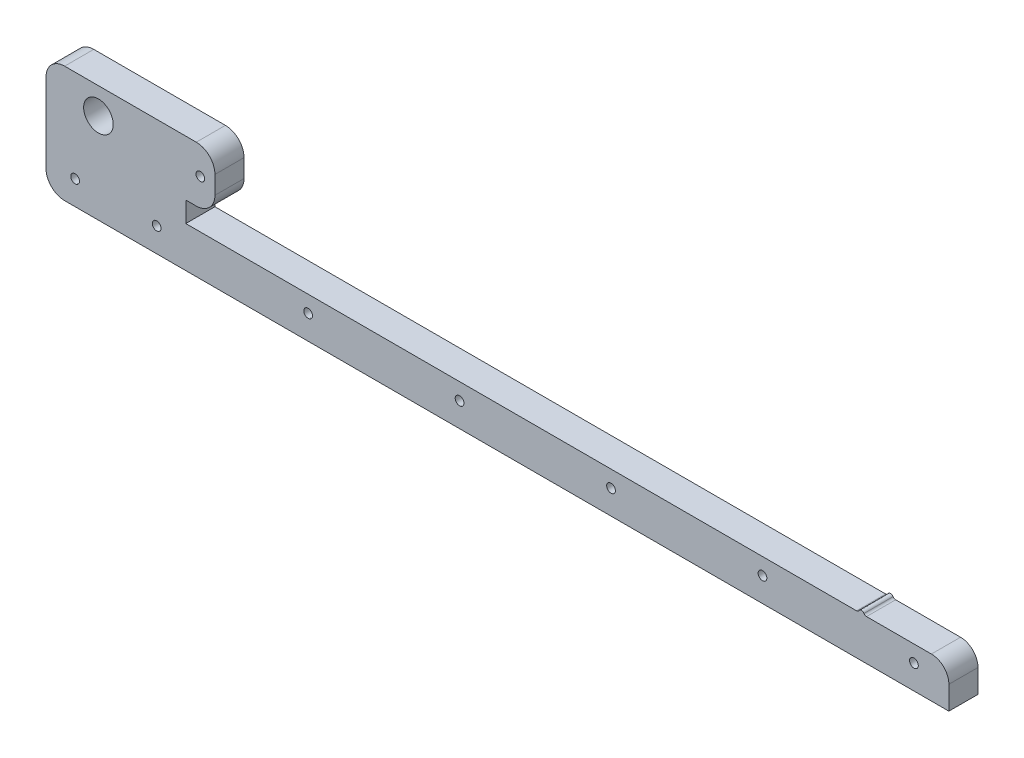
SolidWorks part; units mm, degrees
ref_plane "Płaszczyzna przednia" through (0, 0, 0) normal (0, 0, 1) x (1, 0, 0)
ref_plane "Płaszczyzna górna" through (0, 0, 0) normal (0, 1, 0) x (1, 0, 0)
ref_plane "Płaszczyzna prawa" through (0, 0, 0) normal (1, 0, 0) x (0, 0, -1)
sketch "Szkic1" plane through (0, 0, 0) normal (0, 0, 1) x (1, 0, 0)
  line L0 (656.2388, -438.7456) -> (352.6388, -438.7456)
  line L1 (346.2388, -432.3456) -> (346.2388, -405.1456)
  line L2 (394.2388, -398.7456) -> (397.8388, -398.7456)
  line L3 (394.2388, -424.7456) -> (656.2388, -424.7456)
  line L4 (656.2388, -438.7456) -> (656.2388, -424.7456)
  line L5 (404.2388, -411.3456) -> (404.2388, -405.1456)
  line L6 (397.8388, -417.7456) -> (394.2388, -417.7456)
  line L7 (352.6388, -398.7456) -> (394.2388, -398.7456)
  line L8 (394.2388, -424.7456) -> (394.2388, -417.7456)
  arc A0 (397.8388, -417.7456) -> (404.2388, -411.3456) centre (397.8388, -411.3456) ccw
  arc A1 (352.6388, -438.7456) -> (346.2388, -432.3456) centre (352.6388, -432.3456) cw
  arc A2 (346.2388, -405.1456) -> (352.6388, -398.7456) centre (352.6388, -405.1456) cw
  arc A3 (397.8388, -398.7456) -> (404.2388, -405.1456) centre (397.8388, -405.1456) cw
  dimension "D5" = 7
  dimension "D7" = 6.4
  dimension "D8" = 6.4
  dimension "D1" = 310
  dimension "D2" = 14
  dimension "D3" = 48
  dimension "D4" = 40
  dimension "D6" = 10
extrude "Dodanie-wyciągnięcie1" add sketch "Szkic1" along normal blind 10
sketch "Szkic2" plane through (0, 0, 10) normal (0, 0, 1) x (1, 0, 0)
  line L0 (394.2388, -417.7456) -> (397.8388, -417.7456) construction
  line L1 (404.2388, -411.3456) -> (404.2388, -405.1456) construction
  circle A9 centre (644.2388, -430.4369) radius 1.5
  circle A10 centre (592.2388, -430.4369) radius 1.5
  circle A11 centre (540.2388, -430.4369) radius 1.5
  circle A12 centre (488.2388, -430.4369) radius 1.5
  circle A13 centre (436.2388, -430.4369) radius 1.5
  circle A14 centre (384.2388, -430.4369) radius 1.5
  circle A15 centre (356.2388, -430.4369) radius 1.5
  circle A16 centre (399.2388, -408.2456) radius 1.5
  dimension "D1" = 5
  dimension "D2" = 9.5
extrude "Wytnij-wyciągnięcie1" cut sketch "Szkic2" against normal blind 10
sketch "Szkic5" plane through (0, 0, 0) normal (0, 0, -1) x (-1, 0, 0)
  line L0 (-397.8388, -398.7456) -> (-352.6388, -398.7456) construction
  line L1 (-346.2388, -405.1456) -> (-346.2388, -432.3456) construction
  circle A1 centre (-364.2388, -407.7456) radius 5.075
  dimension "D1" = 9
  dimension "D2" = 18
  dimension "D3" = 10.15
extrude "Wytnij-wyciągnięcie2" cut sketch "Szkic5" against normal blind 10
sketch "Szkic6" plane through (0, 0, 0) normal (0, 0, -1) x (-1, 0, 0)
  line L0 (-656.2388, -430.7456) -> (-656.2388, -424.7456)
  line L1 (-656.2388, -424.7456) -> (-394.2388, -424.7456) construction
  line L2 (-656.2388, -438.7456) -> (-656.2388, -424.7456) construction
  line L3 (-656.2388, -424.7456) -> (-650.2388, -424.7456)
  arc A0 (-650.2388, -424.7456) -> (-656.2388, -430.7456) centre (-650.2388, -430.7456) ccw
  point P9 (-656.2388, -424.7456)
  dimension "D1" = 6
extrude "Wytnij-wyciągnięcie3" cut sketch "Szkic6" against normal blind 10
sketch "Szkic7" plane through (0, 0, 10) normal (0, 0, 1) x (1, 0, 0)
  line L0 (650.2388, -424.7456) -> (394.2388, -424.7456) construction
  line L1 (656.2388, -438.7456) -> (656.2388, -430.7456) construction
  line L4 (624.5068, -424.7456) -> (627.9709, -424.7456)
  arc A0 (627.1049, -424.2456) -> (625.3728, -424.2456) centre (626.2388, -424.7456) ccw
  arc A1 (627.1049, -424.2456) -> (627.9709, -424.7456) centre (627.9709, -423.7456) ccw
  arc A2 (625.3728, -424.2456) -> (624.5068, -424.7456) centre (624.5068, -423.7456) cw
  dimension "D1" = 2
  dimension "D2" = 30
  dimension "D3" = 1
  dimension "D4" = 1
extrude "Dodanie-wyciągnięcie2" add sketch "Szkic7" against normal blind 10
